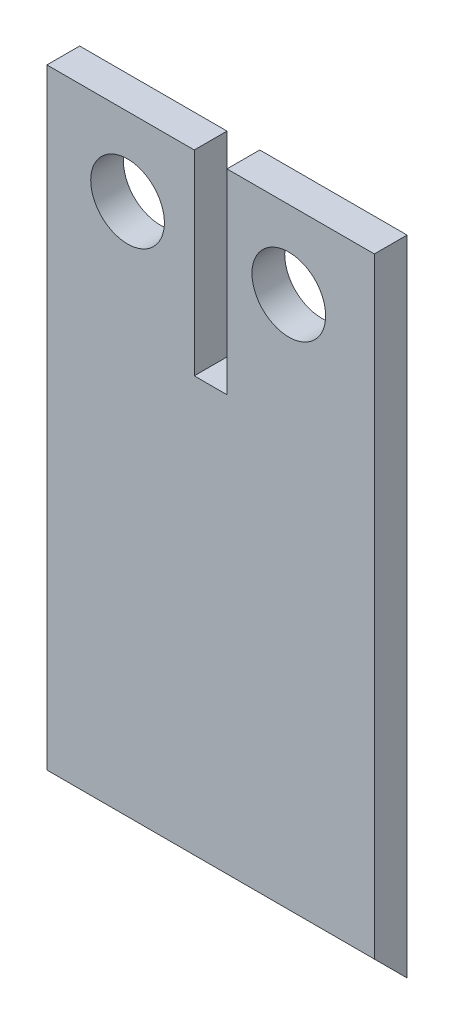
SolidWorks part; units mm, degrees
ref_plane "前视基准面" through (0, 0, 0) normal (0, 0, 1) x (1, 0, 0)
ref_plane "上视基准面" through (0, 0, 0) normal (0, 1, 0) x (1, 0, 0)
ref_plane "右视基准面" through (0, 0, 0) normal (1, 0, 0) x (0, 0, -1)
other "Configuration Table"
ref_plane "基准面1" through (12.2745, 0, 0) normal (1, 0, 0) x (0, 0, -1)
sketch "草图1" plane through (12.2745, 0, 0) normal (1, 0, 0) x (0, 0, -1)
  line L0 (-3.6574, -22.3407) -> (-1.6574, -24.3407)
  line L1 (-1.6574, -24.3407) -> (-1.6574, 14.961)
  line L2 (-1.6574, 14.961) -> (-3.6574, 14.961)
  line L3 (-3.6574, 14.961) -> (-3.6574, -22.3407)
extrude "凸台-拉伸1" add sketch "草图1" against normal blind 20
sketch "草图2" plane through (0, 0, 1.6574) normal (0, 0, -1) x (-1, 0, 0)
  line L0 (-1.2745, 14.961) -> (-3.2745, 14.961)
  line L1 (-3.2745, 14.961) -> (-3.2745, 3.0125)
  line L2 (-3.2745, 3.0125) -> (-1.2745, 3.0125)
  line L3 (-1.2745, 3.0125) -> (-1.2745, 14.961)
extrude "切除-拉伸1" cut sketch "草图2" against normal through all
hole_wizard "Ø4.5 (4.5) 直径孔1" positions "草图4" profile "草图3" hole size "Ø4.5" standard "ANSI Metric"
sketch "草图4" plane through (0, 0, 1.6574) normal (0, 0, -1) x (-1, 0, 0)
  point P0 (2.8005, 10.1998)
  point P1 (-7.0495, 10.1998)
sketch "草图3" plane through (-2.8005, 10.1998, 1.6574) normal (1, 0, 0) x (0, 1, 0)
  line L0 (0, 0) -> (0, 2)
  line L1 (0, 2) -> (2.25, 2)
  line L2 (2.25, 2) -> (2.25, 0)
  line L5 (2.25, 0) -> (0, 0)
  line L11 (0, -6.35) -> (0, 107.95) construction
  dimension "通孔孔直径" = 4.5
  dimension "通孔孔深度" = 2
